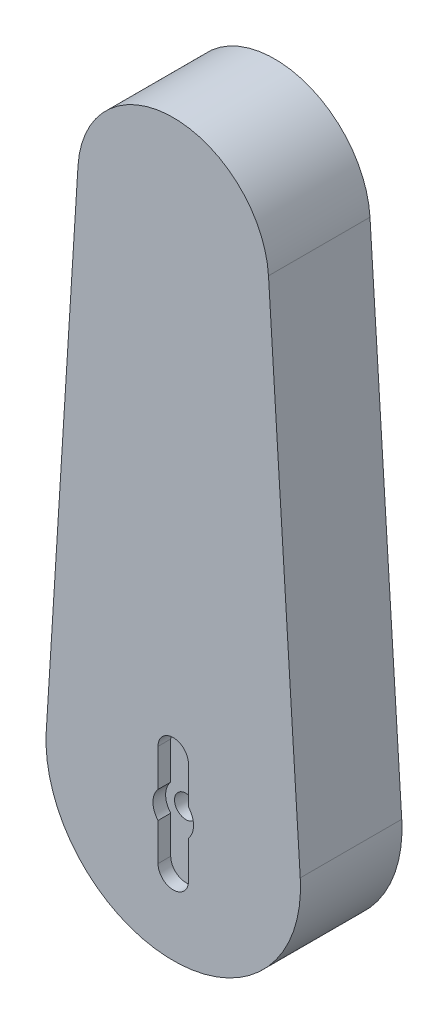
SolidWorks part; units mm, degrees
ref_plane "Front Plane" through (0, 0, 0) normal (0, 0, 1) x (1, 0, 0)
ref_plane "Top Plane" through (0, 0, 0) normal (0, 1, 0) x (1, 0, 0)
ref_plane "Right Plane" through (0, 0, 0) normal (1, 0, 0) x (0, 0, -1)
sketch "Sketch2" plane through (0, 0, 0) normal (0, 0, 1) x (1, 0, 0)
  line L0 (18.7668, 101.1786) -> (25.0224, 1.5715)
  line L1 (-18.7668, 101.1786) -> (-25.0224, 1.5715)
  arc A0 (-25.0224, 1.5715) -> (25.0224, 1.5715) centre (0, 0) ccw
  arc A1 (18.7668, 101.1786) -> (-18.7668, 101.1786) centre (0, 100) ccw
  dimension "D1" = 100
extrude "Boss-Extrude1" add sketch "Sketch2" along normal blind 20
sketch "Sketch3" plane through (0, 0, 20) normal (0, 0, 1) x (1, 0, 0)
  line L0 (0, -10) -> (0, 10) construction
  line L1 (-3, -10) -> (-3, -2.6458)
  line L2 (3, -10) -> (3, -2.6458)
  line L3 (3, 2.6458) -> (3, 10)
  line L4 (-3, 2.6458) -> (-3, 10)
  arc A0 (-3, -10) -> (3, -10) centre (0, -10) ccw
  arc A1 (3, 10) -> (-3, 10) centre (0, 10) ccw
  arc A2 (3, -2.6458) -> (3, 2.6458) centre (0, 0) ccw
  arc A3 (-3, 2.6458) -> (-3, -2.6458) centre (0, 0) ccw
  point P2 (0, 0)
  dimension "D1" = 20
  dimension "D3" = 8
  dimension "D2" = 6
extrude "Cut-Extrude1" cut sketch "Sketch3" against normal blind 2.5
sketch "Sketch4" plane through (0, 0, 17.5) normal (0, 0, 1) x (1, 0, 0)
  circle A0 centre (0, 0) radius 2.25
extrude "Cut-Extrude2" cut sketch "Sketch4" against normal blind 10
sketch "Sketch5" plane through (0, 0, 0) normal (0, 0, -1) x (-1, 0, 0)
  line L1 (-6.4, 82.5) -> (6.4, 82.5)
  line L2 (-6.4, 82.5) -> (-6.4, 106)
  line L4 (6.4, 82.5) -> (6.4, 106)
  line L5 (-6.4, 82.5) -> (2.1943, 106) construction
  line L6 (-6.4, 117.5) -> (6.4, 82.5) construction
  line L7 (-6.4, 106) -> (6.4, 106)
  point P0 (0, 100)
  dimension "D1" = 6.4
  dimension "D2" = 17.5
  dimension "D4" = 6.4
extrude "Cut-Extrude3" cut sketch "Sketch5" against normal blind 16
sketch "Sketch6" plane through (0, 0, 0) normal (0, 0, -1) x (-1, 0, 0)
  circle A0 centre (0, 108.6) radius 1
  circle A1 centre (0, 79.9) radius 1
extrude "Cut-Extrude4" cut sketch "Sketch6" against normal blind 6
equation "\"3mmmm\"=10"
